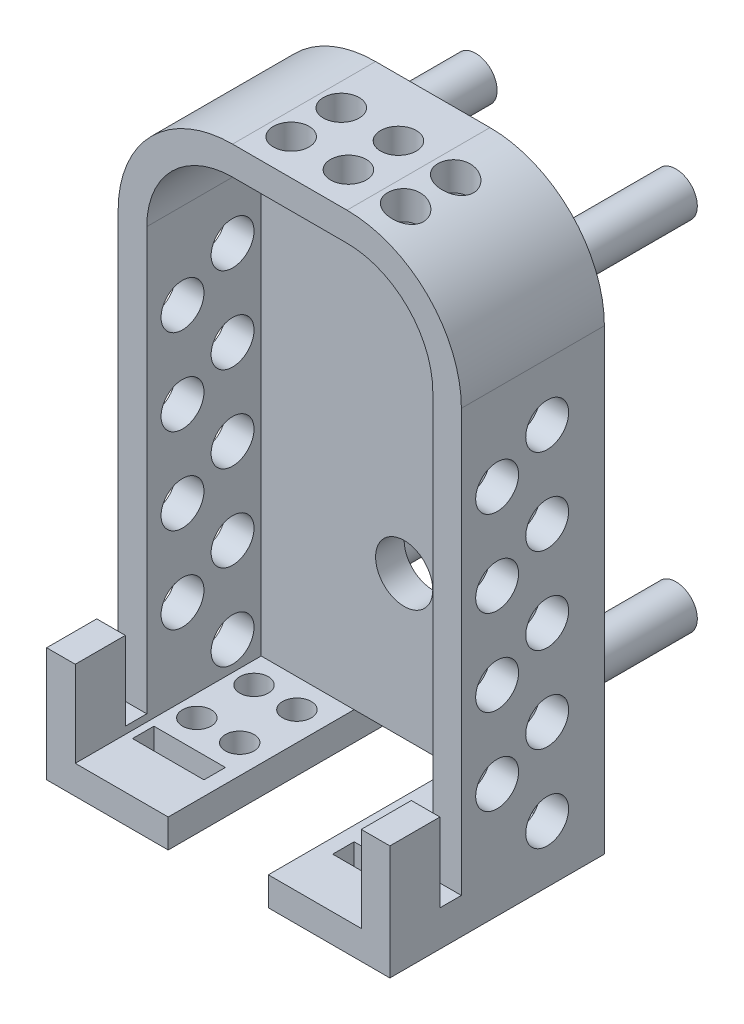
SolidWorks part; units mm, degrees
ref_plane "Plan de face" through (0, 0, 0) normal (0, 0, 1) x (1, 0, 0)
ref_plane "Plan de dessus" through (0, 0, 0) normal (0, 1, 0) x (1, 0, 0)
ref_plane "Plan de droite" through (0, 0, 0) normal (1, 0, 0) x (0, 0, -1)
sketch "Esquisse1" plane through (0, 0, 0) normal (0, 0, 1) x (1, 0, 0)
  line L1 (-12, 20) -> (12, 20)
  line L2 (-12, 20) -> (-12, -20)
  line L3 (-12, -20) -> (12, -20)
  line L4 (12, 20) -> (12, -20)
  line L5 (-12, 20) -> (12, -20) construction
  line L6 (-12, -20) -> (12, 20) construction
  point P0 (0, 0)
  dimension "D1" = 24
  dimension "D2" = 40
extrude "Boss.-Extru.1" add sketch "Esquisse1" along normal blind 10 contours L1 L4 L3 L2
fillet "Congé1" radius 8 2 edges at (12, 20, 5) (-12, 20, 5)
shell "Coque1" thickness 2
sketch "Esquisse2" plane through (0, -20, 0) normal (0, -1, 0) x (1, 0, 0)
  line L0 (-3.5, 0) -> (3.5, 0)
  line L1 (-12, 0) -> (12, 0) construction
  line L2 (3.5, 0) -> (3.5, 10)
  line L3 (-12, 10) -> (12, 10) construction
  line L4 (3.5, 10) -> (-3.5, 10)
  line L5 (-3.5, 0) -> (-3.5, 10)
  point P7 (0, 0)
  dimension "D1" = 7
extrude "Enlèv. mat.-Extru.1" cut sketch "Esquisse2" against normal up to surface (2 mm away) up to face at (0, -18, 6)
sketch "Esquisse3" plane through (12, 0, 0) normal (1, 0, 0) x (0, 0, -1)
  line L0 (0, 12) -> (0, -20) construction
  line L2 (-10, -20) -> (0, -20) construction
  line L3 (-10, 12) -> (-10, -20) construction
  circle A0 centre (-4, -16) radius 1.5
  circle A1 centre (-7.5, -12) radius 1.5
  circle A2 centre (-7.5, -6) radius 1.5
  circle A3 centre (-4, -10) radius 1.5
  circle A4 centre (-7.5, 0) radius 1.5
  circle A5 centre (-4, -4) radius 1.5
  circle A6 centre (-7.5, 6) radius 1.5
  circle A7 centre (-4, 2) radius 1.5
  circle A9 centre (-4, 8) radius 1.5
  circle A10 centre (-7.5, 12) radius 1.5 [skipped]
  dimension "D3" = 3
  dimension "D5" = 8
  dimension "D1" = 4
  dimension "D2" = 4
  dimension "D4" = 2.5
  dimension "D6" = 5
extrude "Enlèv. mat.-Extru.2" cut sketch "Esquisse3" against normal through all
sketch "Esquisse4" plane through (0, 20, 0) normal (0, 1, 0) x (1, 0, 0)
  line L0 (-4, 0) -> (4, 0) construction
  line L1 (-4, 0) -> (-4, -10) construction
  circle A0 centre (-2.4, -4) radius 1.25
  circle A6 centre (1.6, -4) radius 1.25
  circle A7 centre (5.6, -4) radius 1.25
  circle A9 centre (1.6, -7.5) radius 1.25
  circle A10 centre (5.6, -7.5) radius 1.25
  circle A12 centre (-2.4, -7.5) radius 1.25
  circle A13 centre (9.6, -4) radius 1.25 [skipped]
  circle A14 centre (9.6, -7.5) radius 1.25 [skipped]
  dimension "D1" = 2.5
  dimension "D2" = 4
  dimension "D3" = 1.6
  dimension "D5" = 4
  dimension "D4" = 2
extrude "Enlèv. mat.-Extru.3" cut sketch "Esquisse4" against normal blind 13
sketch "Esquisse5" plane through (0, -20, 0) normal (0, -1, 0) x (1, 0, 0)
  line L6 (-12, 10) -> (-3.5, 10) construction
  line L7 (-12, 10) -> (-12, 0) construction
  line L10 (0, -2.7701) -> (0, 9.5539) construction
  circle A0 centre (-8.5, 8) radius 1
  circle A1 centre (-5.5, 8) radius 1
  circle A2 centre (-5.5, 4) radius 1
  circle A3 centre (-8.5, 4) radius 1
  circle A4 centre (8.5, 4) radius 1
  circle A5 centre (5.5, 4) radius 1
  circle A6 centre (5.5, 8) radius 1
  circle A7 centre (8.5, 8) radius 1
  dimension "D1" = 2
  dimension "D2" = 2
  dimension "D3" = 3.5
  dimension "D5" = 2
  dimension "D4" = 2
extrude "Enlèv. mat.-Extru.4" cut sketch "Esquisse5" against normal up to next
sketch "Esquisse7" plane through (0, 0, 10) normal (0, 0, 1) x (1, 0, 0)
  line L0 (-12, 12) -> (-12, -20) construction
  line L1 (-10, 12) -> (-10, -18) construction
  line L2 (12, 12) -> (12, -20) construction
  line L3 (10, 12) -> (10, -18) construction
  line L4 (3.5, -18) -> (10, -18) construction
  line L5 (3.5, -20) -> (12, -20) construction
  line L6 (-10, -18) -> (-3.5, -18) construction
  line L7 (-12, -20) -> (-3.5, -20) construction
  line L8 (3.5, -18) -> (3.5, -20) construction
  line L9 (-3.5, -18) -> (-3.5, -20) construction
  line L10 (-12, -12) -> (-12, -20)
  line L11 (-10, -12) -> (-10, -18)
  line L12 (12, -12) -> (12, -20)
  line L13 (10, -12) -> (10, -18)
  line L14 (3.5, -18) -> (10, -18)
  line L15 (3.5, -20) -> (12, -20)
  line L16 (-10, -18) -> (-3.5, -18)
  line L17 (-12, -20) -> (-3.5, -20)
  line L18 (3.5, -18) -> (3.5, -20)
  line L19 (-3.5, -18) -> (-3.5, -20)
  line L20 (-12, -12) -> (-10, -12)
  line L21 (10, -12) -> (12, -12)
  dimension "D1" = 8
extrude "Boss.-Extru.2" add sketch "Esquisse7" along normal blind 5 and the other way blind 0.5
sketch "Esquisse8" plane through (12, 0, 0) normal (1, 0, 0) x (0, 0, -1)
  line L1 (-10, -12) -> (-15, -12) construction
  line L2 (-11.5, -12) -> (-11.5, -17.5)
  line L3 (-10, -12) -> (-11.5, -12)
  line L4 (-11.5, -17.5) -> (-10, -17.5)
  line L5 (-10, -17.5) -> (-10, -12)
  dimension "D1" = 1.5
  dimension "D2" = 5.5
extrude "Enlèv. mat.-Extru.5" cut sketch "Esquisse8" against normal up to next
sketch "Esquisse9" plane through (0, -20, 0) normal (0, -1, 0) x (1, 0, 0)
  line L2 (4.5, 11.5) -> (9.5, 11.5)
  line L3 (9.5, 11.5) -> (9.5, 10)
  line L4 (4.5, 10) -> (9.5, 10)
  line L5 (4.5, 11.5) -> (4.5, 10)
  line L6 (3.5, 15) -> (12, 15) construction
  line L8 (3.5, 0) -> (3.5, 15) construction
  dimension "D1" = 5
  dimension "D2" = 1.5
  dimension "D3" = 5
  dimension "D4" = 1
extrude "Enlèv. mat.-Extru.6" cut sketch "Esquisse9" against normal up to next
mirror "Symétrie1" about plane through (0, 0, 0) normal (1, 0, 0) of "Enlèv. mat.-Extru.6", "Enlèv. mat.-Extru.5"
sketch "Esquisse10" plane through (0, 0, 2) normal (0, 0, 1) x (1, 0, 0)
  line L0 (-3.5, -18) -> (3.5, -18) construction
  circle A0 centre (0, -8) radius 2
  dimension "D1" = 4
  dimension "D2" = 10
extrude "Enlèv. mat.-Extru.7" cut sketch "Esquisse10" against normal up to next
sketch "Esquisse11" plane through (0, 0, 0) normal (0, 0, -1) x (-1, 0, 0)
  line L0 (0, -22.28) -> (0, 23.9974) construction
  line L1 (-12, 12) -> (-12, -20) construction
  line L2 (4, 20) -> (-4, 20) construction
  circle A0 centre (-7, 12.5) radius 1.5
  circle A4 centre (7, 12.5) radius 1.5
  circle A5 centre (-7, -12.5) radius 1.5
  circle A6 centre (7, -12.5) radius 1.5
  dimension "D1" = 3
  dimension "D3" = 7.5
  dimension "D2" = 5
extrude "Boss.-Extru.3" add sketch "Esquisse11" along normal blind 10
